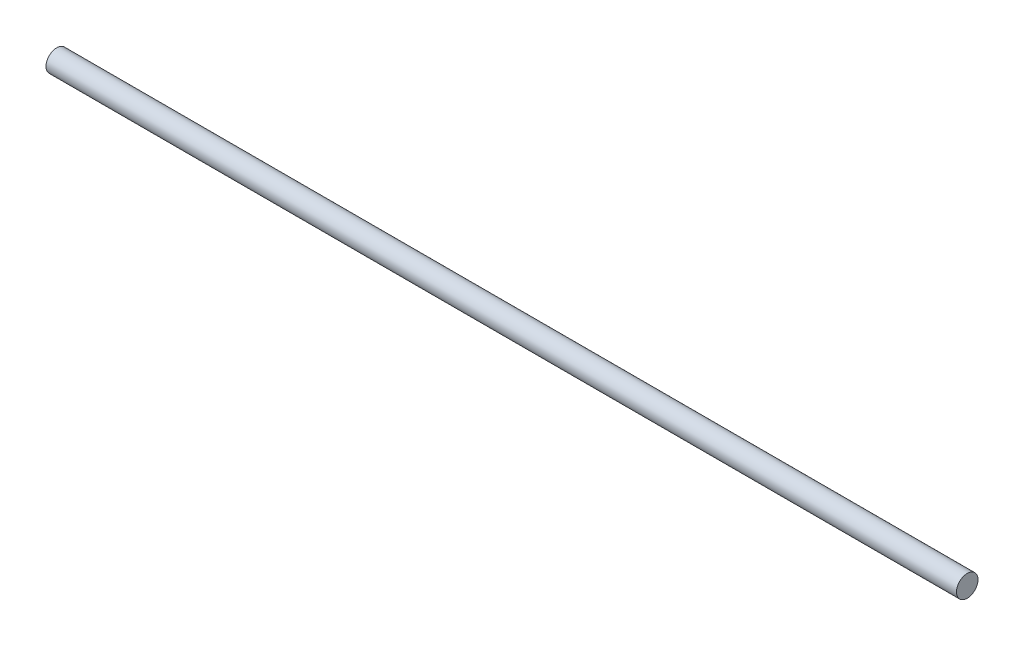
SolidWorks part; units mm, degrees
ref_plane "Спереди" through (0, 0, 0) normal (0, 0, 1) x (1, 0, 0)
ref_plane "Сверху" through (0, 0, 0) normal (0, 1, 0) x (1, 0, 0)
ref_plane "Справа" through (0, 0, 0) normal (1, 0, 0) x (0, 0, -1)
sketch "Эскиз1" plane through (0, 0, 0) normal (1, 0, 0) x (0, 0, -1)
  circle A0 centre (0, 0) radius 4
  dimension "D1" = 8
extrude "Бобышка-Вытянуть1" add sketch "Эскиз1" along normal blind 338
